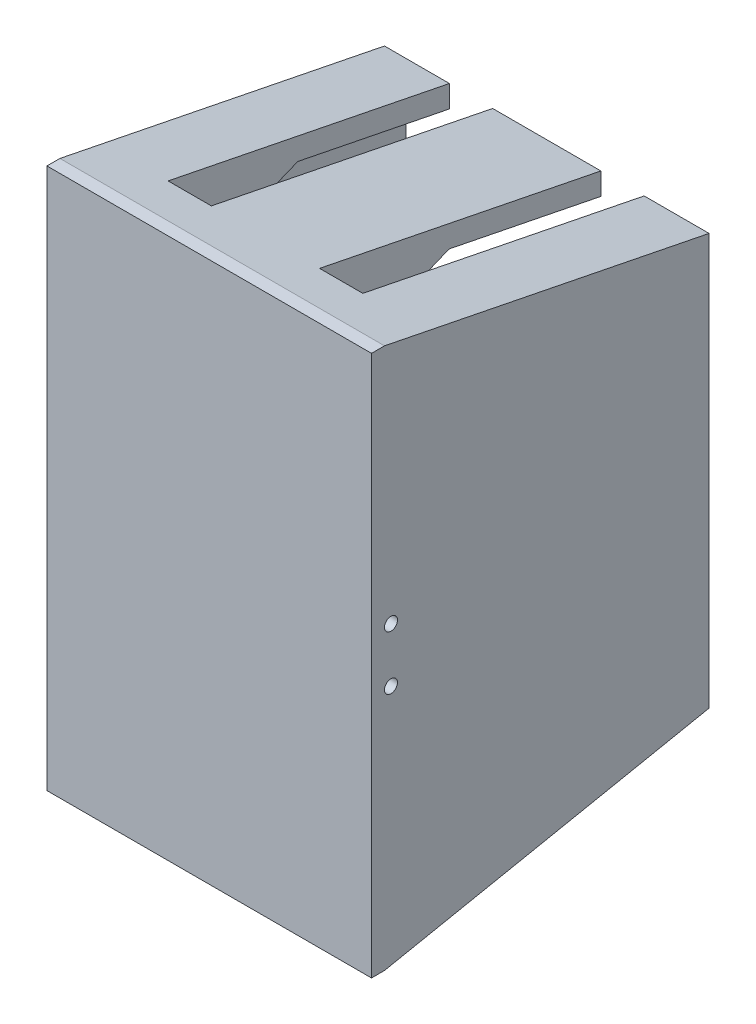
SolidWorks part; units mm, degrees
ref_plane "Front Plane" through (0, 0, 0) normal (0, 0, 1) x (1, 0, 0)
ref_plane "Top Plane" through (0, 0, 0) normal (0, 1, 0) x (1, 0, 0)
ref_plane "Right Plane" through (0, 0, 0) normal (1, 0, 0) x (0, 0, -1)
sketch "Sketch1" plane through (0, 0, 0) normal (1, 0, 0) x (0, 0, -1)
  line L5 (32.5, -32.5) -> (-32.5, 32.5) construction
  line L6 (32.5, 32.5) -> (-32.5, -32.5) construction
  line L9 (-37.5, 32.5) -> (-37.5, -52.5)
  line L12 (37.5, 32.5) -> (37.5, -32.5)
  line L13 (-37.5, 32.5) -> (-37.5, 47.5)
  line L14 (37.5, -32.5) -> (37.5, -37.5)
  line L16 (-37.5, 47.5) -> (-37.5, 62.5)
  line L17 (37.5, 32.5) -> (37.5, 47.5)
  line L18 (37.5, 47.5) -> (-37.5, 62.5)
  line L19 (55, 0) -> (-55, 0) construction
  line L20 (37.5, -47.5) -> (-37.5, -62.5)
  line L21 (37.5, -37.5) -> (37.5, -47.5)
  line L22 (-37.5, -52.5) -> (-37.5, -62.5)
  point P0 (0, 0)
extrude "Boss-Extrude1" add sketch "Sketch1" along normal mid plane 75
shell "Shell1" thickness 5
sketch "Sketch10" plane through (32.5, 0, 0) normal (-1, 0, 0) x (0, 0, 1)
  line L0 (-37.5, 42.401) -> (32.5, 56.401) construction
  line L1 (32.5, -56.401) -> (-37.5, -42.401) construction
  line L2 (-1.9747, -49.506) -> (32.5, -56.401)
  line L3 (32.5, -56.401) -> (32.5, 0)
  line L4 (-2.5, -49.401) -> (-1.9747, -49.506)
  line L5 (-2.5, 49.401) -> (32.5, 56.401)
  line L6 (32.5, 56.401) -> (32.5, 0)
  arc A0 (32.5, 0) -> (-2.5, -49.401) centre (-19.8637, 0) cw
  arc A1 (32.5, 0) -> (-2.5, 49.401) centre (-19.8637, 0) ccw
  line M2 (-37.5, -42.401) -> (32.5, -56.401)
  line M3 (32.5, -56.401) -> (32.5, 56.401)
extrude "Boss-Extrude4" add sketch "Sketch10" along normal up to surface (65 mm away) contours A0 M3 M2 | A1 L5 L6 up to face at (-32.5, 0, -2.5)
sketch "Sketch11" plane through (0, 0, 0) normal (0, 1, 0) x (1, 0, 0)
  line L0 (-22.5, 37.5) -> (-12.5, 37.5)
  line L1 (37.5, 37.5) -> (-37.5, 37.5) construction
  line L3 (-12.5, 37.5) -> (-12.5, -27.5)
  line L4 (-12.5, -27.5) -> (-22.5, -27.5)
  line L5 (-22.5, -27.5) -> (-22.5, 37.5)
  line L7 (0, -41.25) -> (0, 41.25) construction
  line L8 (12.5, -27.5) -> (22.5, -27.5)
  line L9 (12.5, 37.5) -> (12.5, -27.5)
  line L10 (22.5, -27.5) -> (22.5, 37.5)
  line L11 (22.5, 37.5) -> (12.5, 37.5)
extrude "Cut-Extrude4" cut sketch "Sketch11" against normal through all both and the other way through all
sketch "Sketch12" plane through (37.5, 0, 0) normal (1, 0, 0) x (0, 0, -1)
  circle A0 centre (-36, 6.15) radius 1.5
  circle A1 centre (-36, -6.35) radius 1.5
  dimension "D1" = 12.5
sketch "Sketch13" plane through (0, 0, 37.5) normal (0, 0, 1) x (1, 0, 0)
  line L1 (-37.5, 62.5) -> (37.5, 62.5)
  line L2 (-37.5, 62.5) -> (-37.5, -62.5)
  line L3 (-37.5, -62.5) -> (37.5, -62.5)
  line L4 (37.5, 62.5) -> (37.5, -62.5)
extrude "Boss-Extrude5" add sketch "Sketch13" along normal blind 3
extrude "Cut-Extrude5" cut sketch "Sketch12" against normal through all
